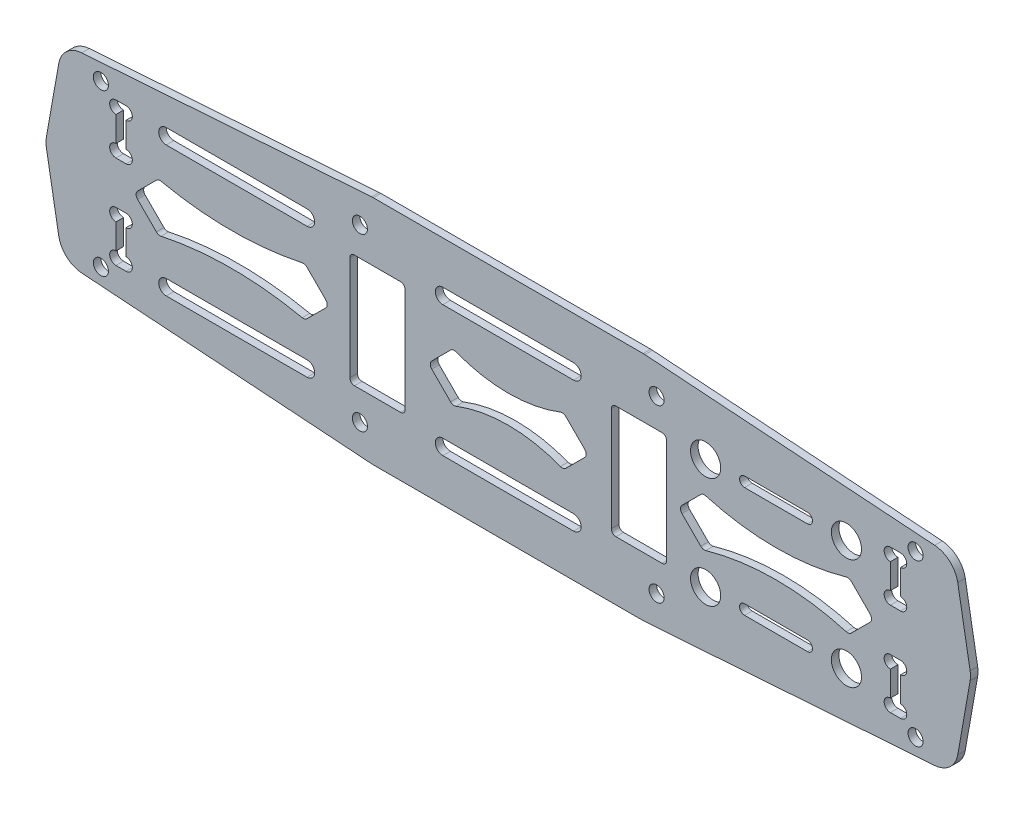
SolidWorks part; units mm, degrees
ref_plane "Alzado" through (0, 0, 0) normal (0, 0, 1) x (1, 0, 0)
ref_plane "Planta" through (0, 0, 0) normal (0, 1, 0) x (1, 0, 0)
ref_plane "Vista lateral" through (0, 0, 0) normal (1, 0, 0) x (0, 0, -1)
ref_plane "Plano1" through (0, 0, 1.5) normal (0, 0, 1) x (1, 0, 0)
sketch "Croquis1" plane through (0, 0, 1.5) normal (0, 0, 1) x (1, 0, 0)
  line L0 (11.4571, 4.4571) -> (15.2071, 0.7071)
  line L1 (15.2071, -0.7071) -> (11.4571, -4.4571)
  line L2 (-11.4571, -4.4571) -> (-15.2071, -0.7071)
  line L3 (-15.2071, 0.7071) -> (-11.4571, 4.4571)
  line L4 (-84.8084, -18.9576) -> (-27.1742, -22.9878)
  line L5 (-26.8254, -23) -> (26.8254, -23)
  line L6 (27.1742, -22.9878) -> (84.8084, -18.9576)
  line L7 (89.3836, -14.8381) -> (91.8469, -0.8682)
  line L8 (91.8469, 0.8682) -> (89.3836, 14.8381)
  line L9 (84.8084, 18.9576) -> (27.1742, 22.9878)
  line L10 (26.8254, 23) -> (-26.8254, 23)
  line L11 (-27.1742, 22.9878) -> (-84.8084, 18.9576)
  line L12 (-89.3836, 14.8381) -> (-91.8469, 0.8682)
  line L13 (-91.8469, -0.8682) -> (-89.3836, -14.8381)
  line L14 (-40, 11.5) -> (-68, 11.5)
  line L15 (-68, 14.5) -> (-40, 14.5)
  line L16 (-40, -14.5) -> (-68, -14.5)
  line L17 (-68, -11.5) -> (-40, -11.5)
  line L18 (13, 11.5) -> (-13, 11.5)
  line L19 (-13, 14.5) -> (13, 14.5)
  line L20 (13, -14.5) -> (-13, -14.5)
  line L21 (-13, -11.5) -> (13, -11.5)
  line L22 (-21.4142, -11.25) -> (-30.5858, -11.25)
  line L23 (-31.5, -10.3358) -> (-31.5, 10.3358)
  line L24 (-30.5858, 11.25) -> (-21.4142, 11.25)
  line L25 (-20.5, 10.3358) -> (-20.5, -10.3358)
  line L26 (20.5, -10.3358) -> (20.5, 10.3358)
  line L27 (21.4142, 11.25) -> (30.5858, 11.25)
  line L28 (31.5, 10.3358) -> (31.5, -10.3358)
  line L29 (30.5858, -11.25) -> (21.4142, -11.25)
  line L30 (59.5, 10) -> (47, 10)
  line L31 (47, 12) -> (59.5, 12)
  line L32 (59.5, -12) -> (47, -12)
  line L33 (47, -10) -> (59.5, -10)
  line L34 (78, -6.75) -> (78, -11.75)
  line L35 (78, -14.25) -> (76, -14.25)
  line L36 (76, -11.75) -> (76, -6.75)
  line L37 (76, -4.25) -> (78, -4.25)
  line L38 (78, 4.25) -> (76, 4.25)
  line L39 (76, 6.75) -> (76, 11.75)
  line L40 (76, 14.25) -> (78, 14.25)
  line L41 (78, 11.75) -> (78, 6.75)
  line L42 (-76, 4.25) -> (-78, 4.25)
  line L43 (-78, 6.75) -> (-78, 11.75)
  line L44 (-78, 14.25) -> (-76, 14.25)
  line L45 (-76, 11.75) -> (-76, 6.75)
  line L46 (-76, -14.25) -> (-78, -14.25)
  line L47 (-78, -11.75) -> (-78, -6.75)
  line L48 (-78, -4.25) -> (-76, -4.25)
  line L49 (-76, -6.75) -> (-76, -11.75)
  line L50 (-40.0429, 4.4571) -> (-36.2929, 0.7071)
  line L51 (-36.2929, -0.7071) -> (-40.0429, -4.4571)
  line L52 (-69.9571, -4.4571) -> (-73.7071, -0.7071)
  line L53 (-73.7071, 0.7071) -> (-69.9571, 4.4571)
  line L54 (68.2071, 4.4571) -> (71.9571, 0.7071)
  line L55 (71.9571, -0.7071) -> (68.2071, -4.4571)
  line L56 (38.2929, -4.4571) -> (34.5429, -0.7071)
  line L57 (34.5429, 0.7071) -> (38.2929, 4.4571)
  arc A0 (-11.4571, 4.4571) -> (-10.3904, 4.6831) centre (-10.75, 3.75) cw
  arc A1 (-10.3904, 4.6831) -> (10.3904, 4.6831) centre (0, 31.6406) ccw
  arc A2 (10.3904, 4.6831) -> (11.4571, 4.4571) centre (10.75, 3.75) cw
  arc A3 (15.2071, 0.7071) -> (15.2071, -0.7071) centre (14.5, 0) cw
  arc A4 (11.4571, -4.4571) -> (10.3904, -4.6831) centre (10.75, -3.75) cw
  arc A5 (10.3904, -4.6831) -> (-10.3904, -4.6831) centre (0, -31.6406) ccw
  arc A6 (-10.3904, -4.6831) -> (-11.4571, -4.4571) centre (-10.75, -3.75) cw
  arc A7 (-15.2071, -0.7071) -> (-15.2071, 0.7071) centre (-14.5, 0) cw
  arc A8 (-27.1742, -22.9878) -> (-26.8254, -23) centre (-26.8254, -18) ccw
  arc A9 (26.8254, -23) -> (27.1742, -22.9878) centre (26.8254, -18) ccw
  arc A10 (84.8084, -18.9576) -> (89.3836, -14.8381) centre (84.4596, -13.9698) ccw
  arc A11 (91.8469, -0.8682) -> (91.8469, 0.8682) centre (86.9229, 0) ccw
  arc A12 (89.3836, 14.8381) -> (84.8084, 18.9576) centre (84.4596, 13.9698) ccw
  arc A13 (27.1742, 22.9878) -> (26.8254, 23) centre (26.8254, 18) ccw
  arc A14 (-26.8254, 23) -> (-27.1742, 22.9878) centre (-26.8254, 18) ccw
  arc A15 (-84.8084, 18.9576) -> (-89.3836, 14.8381) centre (-84.4596, 13.9698) ccw
  arc A16 (-91.8469, 0.8682) -> (-91.8469, -0.8682) centre (-86.9229, 0) ccw
  arc A17 (-89.3836, -14.8381) -> (-84.8084, -18.9576) centre (-84.4596, -13.9698) ccw
  arc A18 (-40, 14.5) -> (-40, 11.5) centre (-40, 13) cw
  arc A19 (-68, 11.5) -> (-68, 14.5) centre (-68, 13) cw
  arc A20 (-40, -11.5) -> (-40, -14.5) centre (-40, -13) cw
  arc A21 (-68, -14.5) -> (-68, -11.5) centre (-68, -13) cw
  arc A22 (13, 14.5) -> (13, 11.5) centre (13, 13) cw
  arc A23 (-13, 11.5) -> (-13, 14.5) centre (-13, 13) cw
  arc A24 (13, -11.5) -> (13, -14.5) centre (13, -13) cw
  arc A25 (-13, -14.5) -> (-13, -11.5) centre (-13, -13) cw
  arc A26 (-20.5, -10.3358) -> (-21.4142, -11.25) centre (-21.4142, -10.3358) cw
  arc A27 (-30.5858, -11.25) -> (-31.5, -10.3358) centre (-30.5858, -10.3358) cw
  arc A28 (-31.5, 10.3358) -> (-30.5858, 11.25) centre (-30.5858, 10.3358) cw
  arc A29 (-21.4142, 11.25) -> (-20.5, 10.3358) centre (-21.4142, 10.3358) cw
  arc A30 (21.4142, -11.25) -> (20.5, -10.3358) centre (21.4142, -10.3358) cw
  arc A31 (20.5, 10.3358) -> (21.4142, 11.25) centre (21.4142, 10.3358) cw
  arc A32 (30.5858, 11.25) -> (31.5, 10.3358) centre (30.5858, 10.3358) cw
  arc A33 (31.5, -10.3358) -> (30.5858, -11.25) centre (30.5858, -10.3358) cw
  arc A34 (59.5, 12) -> (59.5, 10) centre (59.5, 11) cw
  arc A35 (47, 10) -> (47, 12) centre (47, 11) cw
  arc A36 (59.5, -10) -> (59.5, -12) centre (59.5, -11) cw
  arc A37 (47, -12) -> (47, -10) centre (47, -11) cw
  arc A38 (78, -11.75) -> (78, -14.25) centre (78, -13) cw
  arc A39 (76, -14.25) -> (76, -11.75) centre (76, -13) cw
  arc A40 (76, -6.75) -> (76, -4.25) centre (76, -5.5) cw
  arc A41 (78, -4.25) -> (78, -6.75) centre (78, -5.5) cw
  arc A42 (78, 6.75) -> (78, 4.25) centre (78, 5.5) cw
  arc A43 (76, 4.25) -> (76, 6.75) centre (76, 5.5) cw
  arc A44 (76, 11.75) -> (76, 14.25) centre (76, 13) cw
  arc A45 (78, 14.25) -> (78, 11.75) centre (78, 13) cw
  arc A46 (-78, 4.25) -> (-78, 6.75) centre (-78, 5.5) cw
  arc A47 (-78, 11.75) -> (-78, 14.25) centre (-78, 13) cw
  arc A48 (-76, 14.25) -> (-76, 11.75) centre (-76, 13) cw
  arc A49 (-76, 6.75) -> (-76, 4.25) centre (-76, 5.5) cw
  arc A50 (-78, -14.25) -> (-78, -11.75) centre (-78, -13) cw
  arc A51 (-78, -6.75) -> (-78, -4.25) centre (-78, -5.5) cw
  arc A52 (-76, -4.25) -> (-76, -6.75) centre (-76, -5.5) cw
  arc A53 (-76, -11.75) -> (-76, -14.25) centre (-76, -13) cw
  circle A54 centre (39.25, 11) radius 3
  circle A55 centre (67.25, 11) radius 3
  circle A56 centre (39.25, -11) radius 3
  circle A57 centre (67.25, -11) radius 3
  circle A58 centre (81, 16) radius 1.5
  circle A59 centre (29.5, 17) radius 1.5
  circle A60 centre (-29.5, 17) radius 1.5
  circle A61 centre (-81, 16) radius 1.5
  circle A62 centre (-29.5, -17) radius 1.5
  circle A63 centre (29.5, -17) radius 1.5
  circle A64 centre (-81, -16) radius 1.5
  circle A65 centre (81, -16) radius 1.5
  arc A66 (-69.9571, 4.4571) -> (-69.0418, 4.7281) centre (-69.25, 3.75) cw
  arc A67 (-69.0418, 4.7281) -> (-40.9582, 4.7281) centre (-55, 70.6875) ccw
  arc A68 (-40.9582, 4.7281) -> (-40.0429, 4.4571) centre (-40.75, 3.75) cw
  arc A69 (-36.2929, 0.7071) -> (-36.2929, -0.7071) centre (-37, 0) cw
  arc A70 (-40.0429, -4.4571) -> (-40.9582, -4.7281) centre (-40.75, -3.75) cw
  arc A71 (-40.9582, -4.7281) -> (-69.0418, -4.7281) centre (-55, -70.6875) ccw
  arc A72 (-69.0418, -4.7281) -> (-69.9571, -4.4571) centre (-69.25, -3.75) cw
  arc A73 (-73.7071, -0.7071) -> (-73.7071, 0.7071) centre (-73, 0) cw
  arc A74 (71.9571, 0.7071) -> (71.9571, -0.7071) centre (71.25, 0) cw
  arc A75 (68.2071, -4.4571) -> (67.2247, -4.7114) centre (67.5, -3.75) cw
  arc A76 (67.2247, -4.7114) -> (39.2753, -4.7114) centre (53.25, -53.5156) ccw
  arc A77 (39.2753, -4.7114) -> (38.2929, -4.4571) centre (39, -3.75) cw
  arc A78 (34.5429, -0.7071) -> (34.5429, 0.7071) centre (35.25, 0) cw
  arc A79 (38.2929, 4.4571) -> (39.2753, 4.7114) centre (39, 3.75) cw
  arc A80 (39.2753, 4.7114) -> (67.2247, 4.7114) centre (53.25, 53.5156) ccw
  arc A81 (67.2247, 4.7114) -> (68.2071, 4.4571) centre (67.5, 3.75) cw
extrude "Saliente-Extruir1" add sketch "Croquis1" against normal blind 1.5
